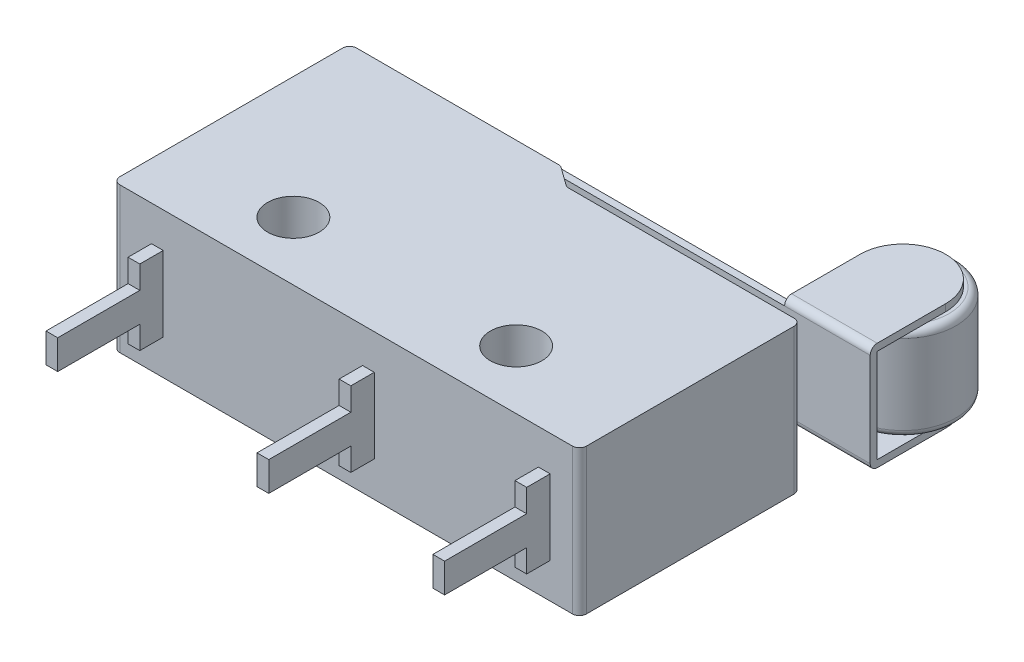
SolidWorks part; units mm, degrees
ref_plane "Plan de face" through (0, 0, 0) normal (0, 0, 1) x (1, 0, 0)
ref_plane "Plan de dessus" through (0, 0, 0) normal (0, 1, 0) x (1, 0, 0)
ref_plane "Plan de droite" through (0, 0, 0) normal (1, 0, 0) x (0, 0, -1)
sketch "Esquisse1" plane through (0, 0, 0) normal (0, 1, 0) x (1, 0, 0)
  line L0 (-9.95, -5.05) -> (-9.95, 5.05)
  line L1 (-9.95, 5.05) -> (-0.95, 5.05)
  line L2 (-0.95, 5.05) -> (-0.05, 4.4)
  line L3 (-0.05, 4.4) -> (9.95, 4.4)
  line L4 (9.95, 4.4) -> (9.95, -5.05)
  line L5 (9.95, -5.05) -> (-9.95, -5.05)
  line L6 (-9.95, 0) -> (9.95, 0) construction
  dimension "D1" = 19.9
  dimension "D2" = 10.1
  dimension "D3" = 9.45
  dimension "D4" = 9
  dimension "D5" = 10
extrude "Boss.-Extru.1" add sketch "Esquisse1" along normal mid plane 6.2
fillet "Congé1" radius 0.3 6 edges at (-0.05, 0, -4.4) (-0.95, 0, -5.05) (-9.95, 0, -5.05) (-9.95, 0, 5.05) (9.95, 0, 5.05) (9.95, 0, -4.4)
sketch "Esquisse2" plane through (0, 0, 0) normal (0, 1, 0) x (1, 0, 0)
  line L0 (0, 0) -> (0, -5.05) construction
  line L1 (-9.65, -5.05) -> (9.65, -5.05) construction
  circle A0 centre (-4.75, -2.55) radius 1.1
  circle A1 centre (4.75, -2.55) radius 1.1
  dimension "D3" = 2.2
  dimension "D1" = 4.75
  dimension "D2" = 2.5
extrude "Enlèv. mat.-Extru.2" cut sketch "Esquisse2" along normal through all both and the other way through all
sketch "Esquisse3" plane through (0, 0, 0) normal (0, 1, 0) x (1, 0, 0)
  line L0 (-1.047, 5.05) -> (-9.65, 5.05) construction
  line L1 (-7.45, 5.05) -> (-7.45, 5.595)
  line L2 (-1.047, 5.05) -> (-9.65, 5.05) construction
  line L3 (-6.995, 6.05) -> (11.55, 6.05)
  line L4 (11.55, 6.05) -> (11.55, 5.75)
  line L5 (11.55, 5.75) -> (-6.995, 5.75)
  line L6 (-7.15, 5.595) -> (-7.15, 5.05)
  line L7 (-7.15, 5.05) -> (-7.45, 5.05)
  line L8 (-9.95, 4.75) -> (-9.95, -4.75) construction
  arc A0 (-7.45, 5.595) -> (-6.995, 6.05) centre (-6.995, 5.595) cw
  arc A1 (-6.995, 5.75) -> (-7.15, 5.595) centre (-6.995, 5.595) ccw
  dimension "D1" = 0.3
  dimension "D2" = 2.5
  dimension "D3" = 19
  dimension "D4" = 0.3
  dimension "D5" = 1
extrude "Boss.-Extru.2" add sketch "Esquisse3" along normal mid plane 4
sketch "Esquisse4" plane through (0, 2, 0) normal (0, 1, 0) x (1, 0, 0)
  line L0 (11.55, 5.75) -> (11.55, 8.97)
  line L1 (11.55, 8.97) -> (7.9, 8.97) construction
  line L2 (7.9, 8.97) -> (7.9, 5.75)
  line L3 (-6.995, 5.75) -> (11.55, 5.75) construction
  line L4 (7.9, 5.75) -> (11.55, 5.75)
  arc A0 (11.55, 8.97) -> (7.9, 8.97) centre (9.725, 8.97) ccw
  dimension "D1" = 1.825
  dimension "D2" = 3.22
extrude "Boss.-Extru.3" add sketch "Esquisse4" along normal blind 0.3
fillet "Congé2" radius 0.3 1 edges at (9.725, 2.3, -5.75)
mirror "Symétrie1" about plane through (0, 0, 0) normal (0, 1, 0) of "Congé2", "Boss.-Extru.3"
ref_plane "Plan1" through (0, 0, -8.97) normal (0, 0, 1) x (1, 0, 0)
sketch "Esquisse6" plane through (0, 0, -8.97) normal (0, 0, 1) x (1, 0, 0)
  line L0 (9.725, 2) -> (9.725, -2)
  line L1 (9.725, -2) -> (11.69, -2)
  line L2 (11.99, -1.7) -> (11.99, 1.7)
  line L3 (11.69, 2) -> (9.725, 2)
  line L4 (11.55, 2) -> (7.9, 2) construction
  line L5 (11.55, -2) -> (7.9, -2) construction
  line L6 (7.9, -2.15) -> (11.55, -2.15) construction
  line L7 (7.9, -2.3) -> (7.9, -2) construction
  line L8 (11.55, -2.3) -> (11.55, -2) construction
  arc A0 (11.69, -2) -> (11.99, -1.7) centre (11.69, -1.7) ccw
  arc A1 (11.99, 1.7) -> (11.69, 2) centre (11.69, 1.7) ccw
  point P19 (9.725, -2.15)
  dimension "D1" = 0.3
  dimension "D2" = 0.3
  dimension "D3" = 2.265
revolve "Révolution1" add sketch "Esquisse6" angle 360 about L0
ref_plane "Plan2" through (8.45, 0, 0) normal (1, 0, 0) x (0, 0, -1)
sketch "Esquisse7" plane through (8.45, 0, 0) normal (1, 0, 0) x (0, 0, -1)
  line L0 (0, 0) -> (-9.55, 0) construction
  line L1 (-5.05, 1.6) -> (-5.05, -1.6)
  line L2 (-5.05, -1.6) -> (-6.05, -1.6)
  line L3 (-6.05, -1.6) -> (-6.05, -0.625)
  line L4 (-6.05, -0.625) -> (-9.55, -0.625)
  line L5 (-9.55, -0.625) -> (-9.55, 0.625)
  line L6 (-9.55, 0.625) -> (-6.05, 0.625)
  line L7 (-6.05, 0.625) -> (-6.05, 1.6)
  line L8 (-6.05, 1.6) -> (-5.05, 1.6)
  line L9 (-5.05, -3.1) -> (-5.05, 3.1) construction
  dimension "D1" = 1
  dimension "D2" = 3.2
  dimension "D3" = 4.5
  dimension "D4" = 1.25
extrude "Boss.-Extru.5" add sketch "Esquisse7" along normal mid plane 0.5
pattern_linear "Répétition linéaire1" count 2 spacing 7.5 along (-1, 0, 0) of "Boss.-Extru.5"
pattern_linear "Répétition linéaire2" count 2 spacing 16.5 along (-1, 0, 0) of "Boss.-Extru.5"
